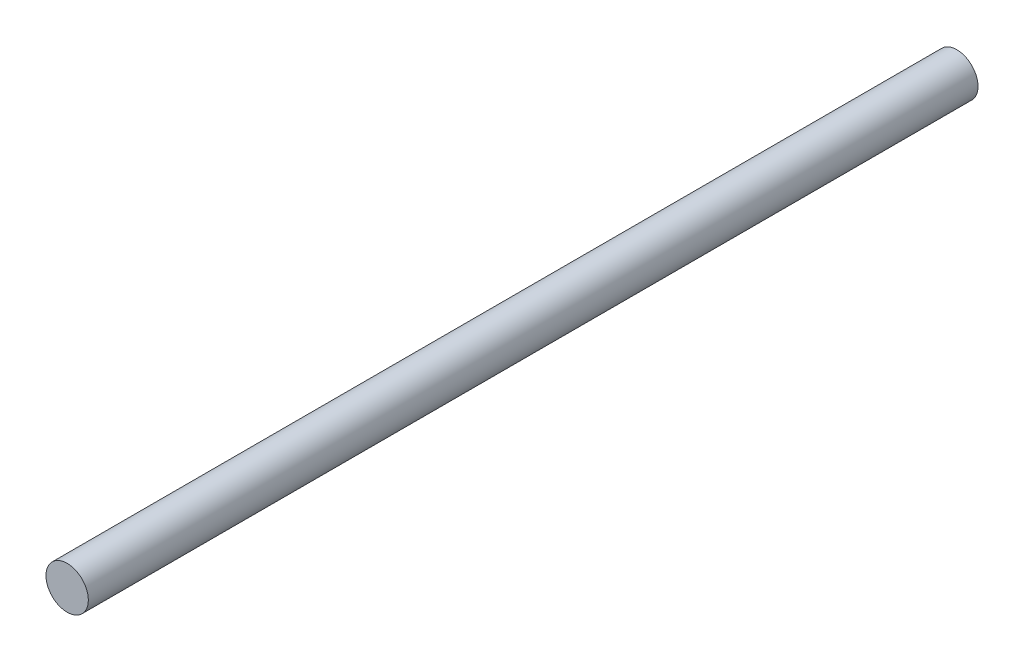
SolidWorks part; units mm, degrees
ref_plane "Спереди" through (0, 0, 0) normal (0, 0, 1) x (1, 0, 0)
ref_plane "Сверху" through (0, 0, 0) normal (0, 1, 0) x (1, 0, 0)
ref_plane "Справа" through (0, 0, 0) normal (1, 0, 0) x (0, 0, -1)
sketch "Эскиз1" plane through (0, 0, 0) normal (0, 0, 1) x (1, 0, 0)
  circle A0 centre (0, 0) radius 2.5
extrude "Вытянуть1" add sketch "Эскиз1" along normal blind 105
